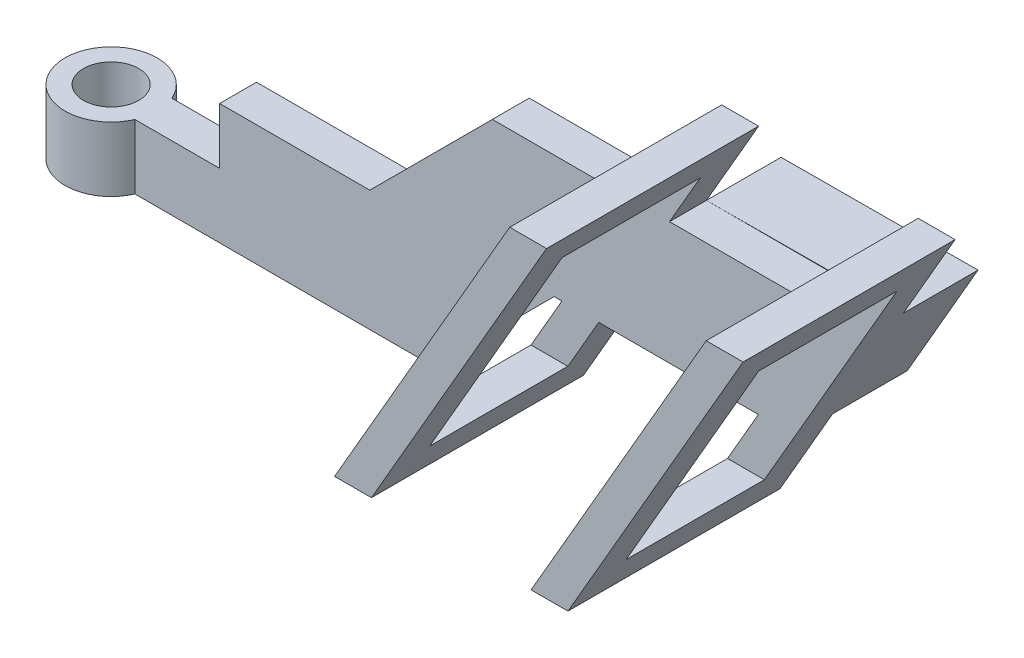
SolidWorks part; units mm, degrees
ref_plane "Front Plane" through (0, 0, 0) normal (0, 0, 1) x (1, 0, 0)
ref_plane "Top Plane" through (0, 0, 0) normal (0, 1, 0) x (1, 0, 0)
ref_plane "Right Plane" through (0, 0, 0) normal (1, 0, 0) x (0, 0, -1)
sketch "Sketch1" plane through (0, 0, 0) normal (0, 1, 0) x (1, 0, 0)
  circle A0 centre (0, 0) radius 3
  circle A1 centre (0, 0) radius 5
  dimension "D1" = 2
  dimension "D2" = 6
extrude "Boss-Extrude1" add sketch "Sketch1" along normal blind 7
sketch "Sketch2" plane through (0, 7, 0) normal (0, 1, 0) x (1, 0, 0)
  line L1 (4.5826, -2) -> (34.5826, -2)
  line L2 (34.5826, -2) -> (34.5826, 2)
  line L3 (34.5826, 2) -> (4.5826, 2)
  circle A1 centre (0, 0) radius 5 construction
  arc A2 (4.5826, 2) -> (4.5826, -2) centre (0, 0) ccw
  circle A3 centre (0, 0) radius 3
  dimension "D1" = 4
  dimension "D2" = 30
extrude "Boss-Extrude2" add sketch "Sketch2" against normal through all
sketch "Sketch3" plane through (0, 0, 2) normal (0, 0, 1) x (1, 0, 0)
  line L0 (4.5826, 0) -> (34.5826, 0) construction
  line L1 (13.7766, 0) -> (30.065, 0)
  line L2 (13.7766, 0) -> (13.7766, 13.1)
  line L3 (13.7766, 13.1) -> (30.065, 13.1)
  line L4 (30.065, 0) -> (30.065, 13.1)
extrude "Boss-Extrude3" add sketch "Sketch3" against normal blind 4
sketch "Sketch4" plane through (0, 0, 2) normal (0, 0, 1) x (1, 0, 0)
  line L0 (4.5826, 0) -> (34.5826, 0) construction
  line L1 (34.5826, 7) -> (30.065, 7)
  line L2 (34.5826, 7) -> (34.5826, 0)
  line L3 (34.5826, 0) -> (30.065, 0)
  line L4 (30.065, 7) -> (30.065, 0)
extrude "Cut-Extrude1" cut sketch "Sketch4" against normal blind 4
sketch "Sketch5" plane through (0, 0, 2) normal (0, 0, 1) x (1, 0, 0)
  line L12 (30.065, 13.1) -> (30.065, 0)
  line L13 (30.065, 0) -> (36.965, 0)
  line L14 (50.065, 13.1) -> (36.765, -0.2) construction
  line L15 (36.965, 0) -> (50.065, 13.1)
  line L16 (50.065, 13.1) -> (76.2256, 13.1)
  line L17 (89.565, 36.2045) -> (70.565, 3.2955) construction
  line L18 (76.2256, 13.1) -> (80.065, 19.75)
  line L19 (80.065, 19.75) -> (80.065, 26.4)
  line L20 (80.065, 26.4) -> (43.365, 26.4)
  line L21 (43.365, 26.4) -> (30.065, 13.1)
extrude "Boss-Extrude4" add sketch "Sketch5" against normal blind 4
sketch "Sketch6" plane through (0, 0, 2) normal (0, 0, 1) x (1, 0, 0)
  line L0 (64.2445, 36.2045) -> (68.2445, 36.2045)
  line L1 (64.2445, 36.2045) -> (45.2445, 3.2955)
  line L2 (68.2445, 36.2045) -> (49.2445, 3.2955)
  line L3 (45.2445, 3.2955) -> (49.2445, 3.2955)
  line L4 (85.565, 36.2045) -> (89.565, 36.2045)
  line L5 (85.565, 36.2045) -> (66.565, 3.2955)
  line L6 (89.565, 36.2045) -> (70.565, 3.2955)
  line L7 (66.565, 3.2955) -> (70.565, 3.2955)
extrude "Boss-Extrude5" add sketch "Sketch6" against normal blind 4
sketch "Sketch7" plane through (0, 0, 2) normal (0, 0, 1) x (1, 0, 0)
  line L0 (68.2445, 36.2045) -> (64.2445, 36.2045)
  line L1 (68.2445, 36.2045) -> (65.9351, 32.2045)
  line L2 (64.2445, 36.2045) -> (61.9351, 32.2045)
  line L3 (65.9351, 32.2045) -> (61.9351, 32.2045)
  line L4 (64.2445, 36.2045) -> (58.5838, 26.4) construction
  line L5 (85.565, 36.2045) -> (89.565, 36.2045)
  line L6 (85.565, 36.2045) -> (83.2556, 32.2045)
  line L7 (89.565, 36.2045) -> (87.2556, 32.2045)
  line L8 (83.2556, 32.2045) -> (87.2556, 32.2045)
  line L9 (70.565, 3.2955) -> (89.565, 36.2045) construction
  line L10 (66.565, 3.2955) -> (70.565, 3.2955)
  line L11 (66.565, 3.2955) -> (68.8744, 7.2955)
  line L12 (70.565, 3.2955) -> (72.8744, 7.2955)
  line L13 (68.8744, 7.2955) -> (72.8744, 7.2955)
  line L14 (70.565, 3.2955) -> (89.565, 36.2045) construction
  line L15 (45.2445, 3.2955) -> (49.2445, 3.2955)
  line L16 (45.2445, 3.2955) -> (47.5539, 7.2955)
  line L17 (49.2445, 3.2955) -> (51.5539, 7.2955)
  line L18 (47.5539, 7.2955) -> (51.5539, 7.2955)
  line L19 (49.2445, 3.2955) -> (54.9051, 13.1) construction
  dimension "D1" = 4
extrude "Boss-Extrude6" add sketch "Sketch7" along normal blind 19
sketch "Sketch8" plane through (0, 0, 21) normal (0, 0, 1) x (1, 0, 0)
  line L0 (64.2445, 36.2045) -> (68.2445, 36.2045)
  line L1 (64.2445, 36.2045) -> (45.2445, 3.2955)
  line L2 (68.2445, 36.2045) -> (49.2445, 3.2955)
  line L3 (45.2445, 3.2955) -> (49.2445, 3.2955)
  line L4 (85.565, 36.2045) -> (89.565, 36.2045)
  line L5 (85.565, 36.2045) -> (66.565, 3.2955)
  line L6 (89.565, 36.2045) -> (70.565, 3.2955)
  line L7 (66.565, 3.2955) -> (70.565, 3.2955)
extrude "Boss-Extrude7" add sketch "Sketch8" against normal blind 4
sketch "Sketch9" plane through (0, 0, -2) normal (0, 0, -1) x (-1, 0, 0)
  line L0 (-54.9051, 13.1) -> (-62.5838, 26.4)
  line L1 (-54.9051, 13.1) -> (-76.274, 13.1838)
  line L2 (-62.5838, 26.4) -> (-83.9527, 26.4838)
  line L3 (-76.274, 13.1838) -> (-83.9527, 26.4838)
  line L4 (-70.565, 3.2955) -> (-89.565, 36.2045) construction
extrude "Boss-Extrude8" add sketch "Sketch9" along normal blind 8.1
